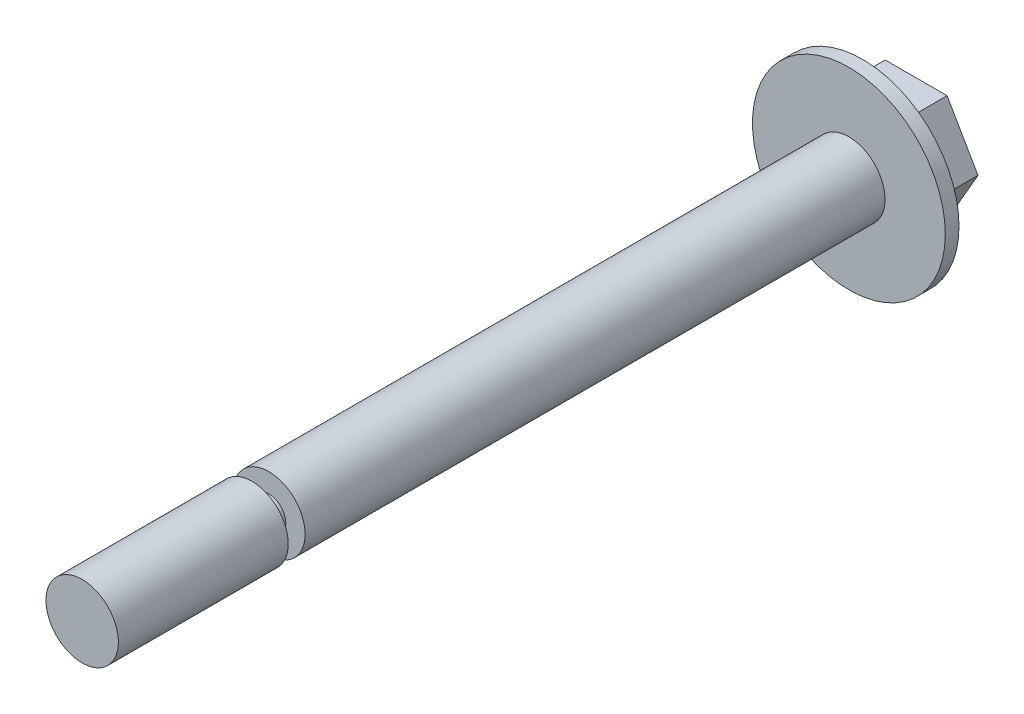
SolidWorks part; units mm, degrees
material "Ti-6Al-4VSolution treated and aged (SS)"
ref_plane "Front Plane" through (0, 0, 0) normal (0, 0, 1) x (1, 0, 0)
ref_plane "Top Plane" through (0, 0, 0) normal (0, 1, 0) x (1, 0, 0)
ref_plane "Right Plane" through (0, 0, 0) normal (1, 0, 0) x (0, 0, -1)
sketch "Sketch1" plane through (0, 0, 0) normal (0, 0, 1) x (1, 0, 0)
  line L1 (3.6662, 0) -> (1.8331, 3.175)
  line L2 (1.8331, 3.175) -> (-1.8331, 3.175)
  line L3 (-1.8331, 3.175) -> (-3.6662, 0)
  line L4 (-3.6662, 0) -> (-1.8331, -3.175)
  line L5 (-1.8331, -3.175) -> (1.8331, -3.175)
  line L6 (1.8331, -3.175) -> (3.6662, 0)
  circle A0 centre (0, 0) radius 3.175 construction
  dimension "D1" = 6.35
extrude "Boss-Extrude1" add sketch "Sketch1" along normal blind 3.175
sketch "Sketch2" plane through (0, 0, 3.175) normal (0, 0, 1) x (1, 0, 0)
  circle A0 centre (0, 0) radius 5.715
  dimension "D1" = 11.43
extrude "Boss-Extrude2" add sketch "Sketch2" along normal blind 0.8128
sketch "Sketch3" plane through (0, 0, 0) normal (1, 0, 0) x (0, 0, -1)
  line L0 (-3.9878, 0) -> (-49.4378, 0)
  line L1 (-3.9878, 5.715) -> (-3.9878, -5.715) construction
  line L2 (2.1933, 0) -> (-2.1933, 0) construction
  line L3 (-3.9878, 0) -> (-3.9878, 2.145)
  line L4 (-3.9878, 2.145) -> (-38.3678, 2.145)
  line L5 (-38.3678, 2.145) -> (-38.3678, 1)
  line L6 (-38.3678, 1) -> (-39.3678, 1)
  line L7 (-39.3678, 1) -> (-39.3678, 2.145)
  line L8 (-39.3678, 2.145) -> (-49.4378, 2.145)
  line L9 (-49.4378, 2.145) -> (-49.4378, 0)
  dimension "D1" = 45.45
  dimension "D2" = 2.145
  dimension "D3" = 1
  dimension "D4" = 34.38
  dimension "D5" = 1
revolve "Revolve1" add sketch "Sketch3" angle 360 about L0
equation "\"ShankLength\"= 1.75in'Max of 1.75 in, can be sized down"
equation "\"ThreadLength\"= .078in'Min of 0.078 in, can be sized up"
